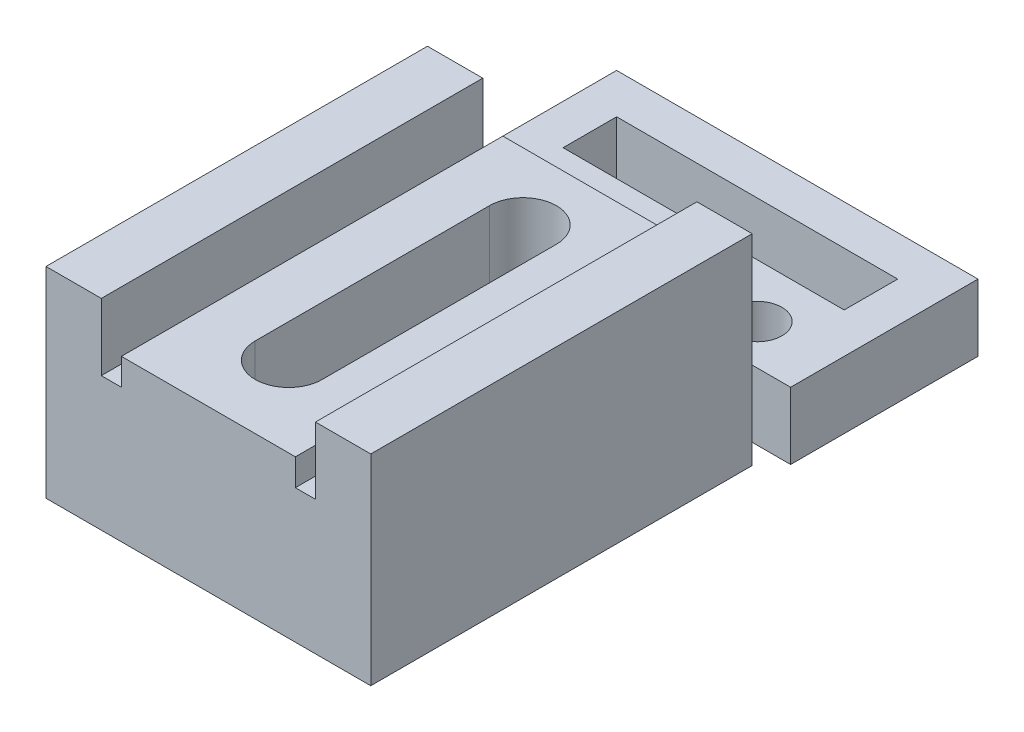
SolidWorks part; units mm, degrees
ref_plane "Alzado" through (0, 0, 0) normal (0, 0, 1) x (1, 0, 0)
ref_plane "Planta" through (0, 0, 0) normal (0, 1, 0) x (1, 0, 0)
ref_plane "Vista lateral" through (0, 0, 0) normal (1, 0, 0) x (0, 0, -1)
sketch "Croquis1" plane through (0, 0, 0) normal (1, 0, 0) x (0, 0, -1)
  line L0 (49.6616, 6.8488) -> (49.6616, -3.1512)
  line L2 (79.6616, -3.1512) -> (79.6616, 6.8488)
  line L3 (79.6616, 6.8488) -> (49.6616, 6.8488)
  line L7 (49.6616, -3.1512) -> (79.6616, -3.1512)
  dimension "D1" = 10
  dimension "D2" = 30
extrude "Saliente-Extruir1" add sketch "Croquis1" against normal blind 18
sketch "Croquis2" plane through (0, 13.6977, -49.6616) normal (0, 0, -1) x (1, 0, 0)
  line L0 (-17, 9.8488) -> (-17, 6.8488)
  line L1 (-17, 6.8488) -> (-1, 6.8488)
  line L2 (-1, 6.8488) -> (-1, 9.8488)
  line L3 (-1, 9.8488) -> (-17, 9.8488)
  line L7 (-18, 6.8488) -> (0, 6.8488) construction
  dimension "D1" = 3
  dimension "D2" = 16
extrude "Cortar-Extruir1" cut sketch "Croquis2" along normal through all
hole_wizard "Diámetro de taladro Ø5.0 (5)1" positions "Croquis4" profile "Croquis3" hole size "Ø5.0" standard "Ansi Metric" end condition through all
sketch "Croquis4" plane through (0, 3.8488, 0) normal (0, 1, 0) x (1, 0, 0)
  point P0 (-9, 65.1616)
sketch "Croquis3" plane through (-9, 3.8488, -65.1616) normal (1, 0, 0) x (0, 0, 1)
  line L0 (0, 0) -> (0, 7)
  line L1 (0, 7) -> (2.5, 7)
  line L2 (2.5, 7) -> (2.5, 0)
  line L5 (2.5, 0) -> (0, 0)
  line L11 (0, -6.35) -> (0, 7) construction
  dimension "Diámetro de taladro hasta el siguiente" = 5
  dimension "Profundidad de taladro hasta el siguiente" = 7
hole_wizard "Diámetro de taladro Ø5.0 (5)2" positions "Croquis6" profile "Croquis5" hole size "Ø5.0" standard "Ansi Metric" end condition through all
sketch "Croquis6" plane through (0, 3.8488, 0) normal (0, 1, 0) x (1, 0, 0)
  point P0 (-9, 73.1616)
sketch "Croquis5" plane through (-9, 3.8488, -73.1616) normal (1, 0, 0) x (0, 0, 1)
  line L0 (0, 0) -> (0, 7)
  line L1 (0, 7) -> (2.5, 7)
  line L2 (2.5, 7) -> (2.5, 0)
  line L5 (2.5, 0) -> (0, 0)
  line L11 (0, -6.35) -> (0, 107.95) construction
  dimension "Diámetro de taladro hasta el siguiente" = 5
  dimension "Profundidad de taladro hasta el siguiente" = 7
sketch "Croquis7" plane through (0, -3.1512, 0) normal (0, -1, 0) x (1, 0, 0)
  line L0 (-17, -82.6616) -> (-9, -82.6616) construction
  line L6 (-18, -79.6616) -> (-22.5, -79.6616) construction
  line L7 (-22.5, -79.6616) -> (-22.5, -93.6616) construction
  line L8 (-17, -82.6616) -> (-17, -93.6616) construction
  line L9 (-22.5, -93.6616) -> (4.5, -93.6616)
  line L10 (-22.5, -93.6616) -> (-22.5, -79.6616)
  line L11 (-22.5, -79.6616) -> (-18, -79.6616)
  line L12 (-9, -93.6616) -> (-9, -82.6616) construction
  line L13 (4.5, -93.6616) -> (4.5, -79.6616)
  line L15 (0, -79.6616) -> (4.5, -79.6616)
  line L19 (0, -79.6616) -> (0, -49.6616)
  line L20 (0, -49.6616) -> (-18, -49.6616)
  line L21 (-18, -49.6616) -> (-18, -79.6616)
  line L22 (-18, -79.6616) -> (0, -79.6616)
  line L23 (0, -79.6616) -> (0, -49.6616)
  line L24 (0, -49.6616) -> (-18, -49.6616)
  line L25 (-18, -49.6616) -> (-18, -78.779)
  circle A0 centre (-17, -82.6616) radius 1.85
  circle A1 centre (-1, -82.6616) radius 1.85
  circle M29 centre (-9, -73.1616) radius 2.5
  circle M30 centre (-9, -65.1616) radius 2.5
  line M31 (0, -79.6616) -> (0, -49.6616)
  line M32 (0, -49.6616) -> (-18, -49.6616)
  line M33 (-18, -49.6616) -> (-18, -79.6616)
  line M34 (-18, -79.6616) -> (0, -79.6616)
  dimension "D3" = 3.7
  dimension "D2" = 14
  dimension "D4" = 11
  dimension "D5" = 8
  dimension "D6" = 0
extrude "Saliente-Extruir2" add sketch "Croquis7" along normal blind 5 contours M34 M31 M32 M33 M30 M29 | L15 L11 L10 L9 L13 A0 A1 M34
sketch "Croquis9" plane through (0, -8.1512, 0) normal (0, -1, 0) x (-1, 0, 0)
  line L0 (19.5, 86.6616) -> (-1.5, 86.6616)
  line L4 (22.5, 93.6616) -> (22.5, 79.6616) construction
  line L5 (22.5, 93.6616) -> (-4.5, 93.6616) construction
  line L7 (-4.5, 93.6616) -> (-4.5, 79.6616) construction
  line L9 (0, 79.6616) -> (-4.5, 79.6616) construction
  line L18 (-1.5, 86.6616) -> (-1.5, 90.6616)
  line L19 (-1.5, 90.6616) -> (19.5, 90.6616)
  line L20 (19.5, 90.6616) -> (19.5, 86.6616)
  dimension "D4" = 7
  dimension "D1" = 3
  dimension "D2" = 3
  dimension "D3" = 3
extrude "Cortar-Extruir3" cut sketch "Croquis9" against normal up to next
sketch "Croquis11" plane through (0, 6.8488, 0) normal (0, 1, 0) x (1, 0, 0)
  line L16 (-21.1318, 49.6616) -> (-18, 49.6616)
  line L23 (-21.1318, 49.6616) -> (-21.1318, 78.1616)
  line L25 (-18, 78.1616) -> (-18, 49.6616)
  line L26 (-18, 49.6616) -> (-9, 49.6616) construction
  line L28 (-9, 45.4271) -> (-9, 49.6616) construction
  line L32 (-9, 79.6616) -> (-9, 78.1616) construction
  line L34 (-18, 78.1616) -> (-21.1318, 78.1616)
  line L35 (3.1318, 49.6616) -> (3.1318, 78.1616)
  line L36 (0, 78.1616) -> (3.1318, 78.1616)
  line L37 (0, 78.1616) -> (0, 49.6616)
  line L38 (3.1318, 49.6616) -> (0, 49.6616)
  dimension "D1" = 1.5
sketch "Croquis12" plane through (-18, 0, 0) normal (-1, 0, 0) x (0, 0, 1)
  line L1 (-79.6616, -3.1512) -> (-78.1616, -3.1512)
  line L2 (-79.6616, -3.1512) -> (-79.6616, 6.8488)
  line L3 (-79.6616, 6.8488) -> (-78.1616, 6.8488)
  line L4 (-78.1616, -3.1512) -> (-78.1616, 6.8488)
extrude "Cortar-Extruir4" cut sketch "Croquis12" against normal up to next
extrude "Saliente-Extruir4" add sketch "Croquis11" against normal up to surface (15 mm away) contours L16 L25 L34 L23 | L35 L36 L37 L38 up to face at (-9, -8.1512, -88.6616)
sketch "Croquis13" plane through (0, 3.8488, 0) normal (0, 1, 0) x (1, 0, 0)
  line L0 (-1, 49.6616) -> (-17, 49.6616) construction
  line L1 (-17, 78.1616) -> (-15.5, 78.1616)
  line L2 (-17, 78.1616) -> (-17, 49.6616)
  line L3 (-17, 49.6616) -> (-15.5, 49.6616)
  line L4 (-15.5, 78.1616) -> (-15.5, 49.6616)
  line L5 (-9, 78.1616) -> (-9, 76.9241) construction
  line L6 (-1, 78.1616) -> (-17, 78.1616) construction
  line L7 (-1, 49.6616) -> (-2.5, 49.6616)
  line L8 (-2.5, 78.1616) -> (-2.5, 49.6616)
  line L9 (-1, 78.1616) -> (-2.5, 78.1616)
  line L10 (-1, 78.1616) -> (-1, 49.6616)
  dimension "D1" = 1.5
extrude "Cortar-Extruir5" cut sketch "Croquis13" against normal blind 2
sketch "Croquis14" plane through (0, 3.8488, 0) normal (0, 1, 0) x (1, 0, 0)
  line L0 (-9, 73.1616) -> (-9, 55.6616) construction
  line L1 (-9, 64.4116) -> (-12.7237, 64.4116) construction
  line L2 (-6.5, 55.6616) -> (-6.5, 73.1616)
  line L3 (-11.5, 73.1616) -> (-11.5, 55.6616)
  circle A3 centre (-9, 73.1616) radius 2.5 construction
  arc A4 (-6.5, 73.1616) -> (-11.5, 73.1616) centre (-9, 73.1616) ccw
  arc A5 (-6.5, 55.6616) -> (-11.5, 55.6616) centre (-9, 55.6616) cw
  dimension "D1" = 17.5
extrude "Cortar-Extruir6" cut sketch "Croquis14" against normal up to next (12 mm away) from surface at 3 contours L2 A4 L3 A5 starting at face at (-19.0659, 6.8488, -63.9116)
